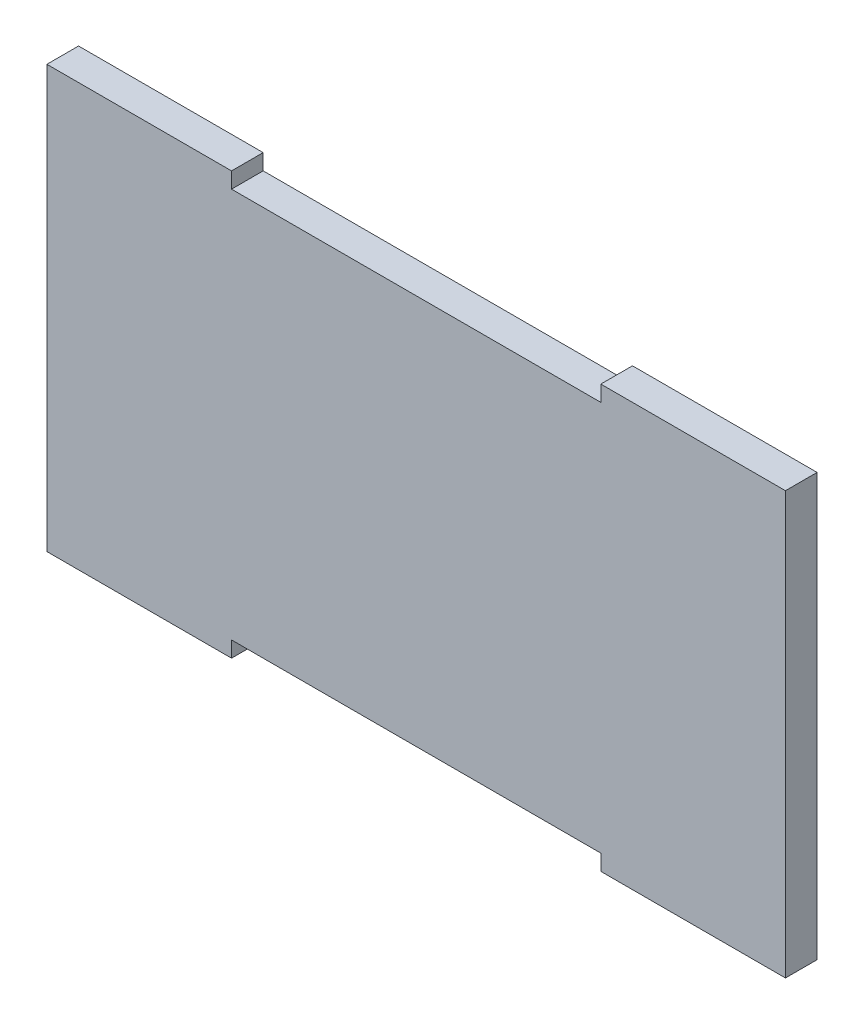
SolidWorks part; units mm, degrees
ref_plane "Plano frontal" through (0, 0, 0) normal (0, 0, 1) x (1, 0, 0)
ref_plane "Plano superior" through (0, 0, 0) normal (0, 1, 0) x (1, 0, 0)
ref_plane "Plano direito" through (0, 0, 0) normal (1, 0, 0) x (0, 0, -1)
sketch "Esboço1" plane through (0, 0, 0) normal (0, 0, 1) x (1, 0, 0)
  line L0 (-35, 40) -> (-35, -40) construction
  line L2 (70, -40) -> (70, 40)
  line L3 (70, 40) -> (35, 40)
  line L4 (-70, -40) -> (-70, 40)
  line L5 (70, -40) -> (-70, 40) construction
  line L6 (70, 40) -> (-70, -40) construction
  line L7 (35, 40) -> (35, -40) construction
  line L8 (0, 0) -> (-70, 0) construction
  line L9 (-35, 37) -> (-35, 40)
  line L10 (35, 40) -> (35, 37)
  line L11 (0, 0) -> (70, 0) construction
  line L12 (-35, 37) -> (35, 37)
  line L13 (-35, 40) -> (-70, 40)
  line L14 (70, -40) -> (35, -40)
  line L15 (35, -40) -> (35, -37)
  line L16 (-35, -37) -> (35, -37)
  line L17 (-35, -37) -> (-35, -40)
  line L18 (-35, -40) -> (-70, -40)
  point P0 (0, 0)
  dimension "D1" = 80
  dimension "D2" = 140
  dimension "D3" = 35
  dimension "D4" = 35
  dimension "D5" = 3
  dimension "D6" = 3
extrude "Ressalto-extrusão1" add sketch "Esboço1" along normal blind 6 contours L13 L4 L18 L17 L16 L15 L14 L2 L3 L10 L12 L9
